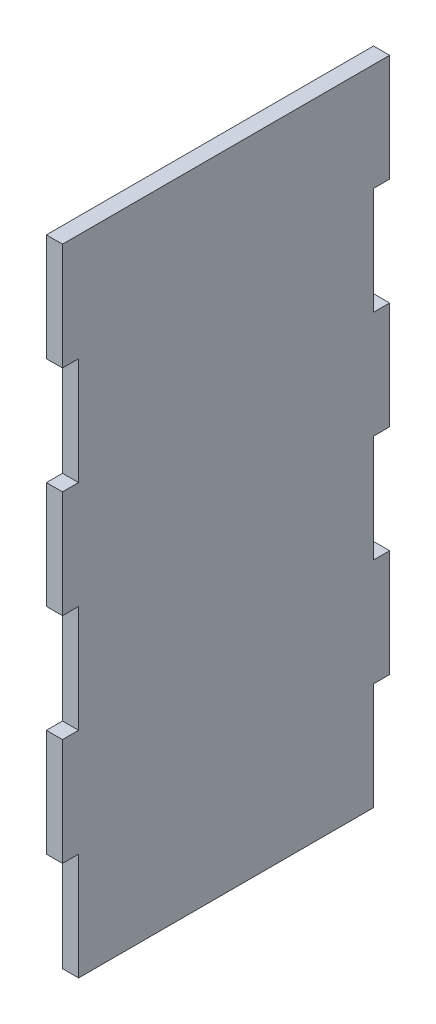
SolidWorks part; units mm, degrees
material "Acrilico TEC"
ref_plane "Front Plane" through (0, 0, 0) normal (0, 0, 1) x (1, 0, 0)
ref_plane "Top Plane" through (0, 0, 0) normal (0, 1, 0) x (1, 0, 0)
ref_plane "Right Plane" through (0, 0, 0) normal (1, 0, 0) x (0, 0, -1)
sketch "Sketch1" plane through (0, 0, 0) normal (1, 0, 0) x (0, 0, -1)
  line L0 (-27.5, 0) -> (27.5, 0)
  line L1 (27.5, 0) -> (27.5, 20)
  line L2 (27.5, 20) -> (30.5, 20)
  line L3 (30.5, 20) -> (30.5, 40)
  line L4 (30.5, 40) -> (27.5, 40)
  line L5 (27.5, 40) -> (27.5, 60)
  line L6 (27.5, 60) -> (30.5, 60)
  line L7 (30.5, 60) -> (30.5, 80)
  line L8 (30.5, 80) -> (27.5, 80)
  line L9 (27.5, 80) -> (27.5, 100)
  line L10 (27.5, 100) -> (30.5, 100)
  line L11 (0, 90) -> (0, 0) construction
  line L12 (-27.5, 80) -> (-27.5, 100)
  line L13 (-30.5, 80) -> (-27.5, 80)
  line L14 (-30.5, 60) -> (-30.5, 80)
  line L15 (-27.5, 60) -> (-30.5, 60)
  line L16 (-27.5, 40) -> (-27.5, 60)
  line L17 (-30.5, 40) -> (-27.5, 40)
  line L18 (-30.5, 20) -> (-30.5, 40)
  line L19 (-27.5, 20) -> (-30.5, 20)
  line L20 (-27.5, 0) -> (-27.5, 20)
  line L21 (30.5, 100) -> (30.5, 120)
  line L22 (30.5, 120) -> (-30.5, 120)
  line L23 (-27.5, 100) -> (-30.5, 100)
  line L24 (-30.5, 100) -> (-30.5, 120)
  point P28 (0, 120)
  dimension "D1" = 27.5
  dimension "D2" = 20
  dimension "D3" = 20
  dimension "D4" = 20
  dimension "D5" = 20
  dimension "D6" = 20
  dimension "D7" = 3
  dimension "D8" = 20
extrude "Boss-Extrude1" add sketch "Sketch1" along normal blind 3
